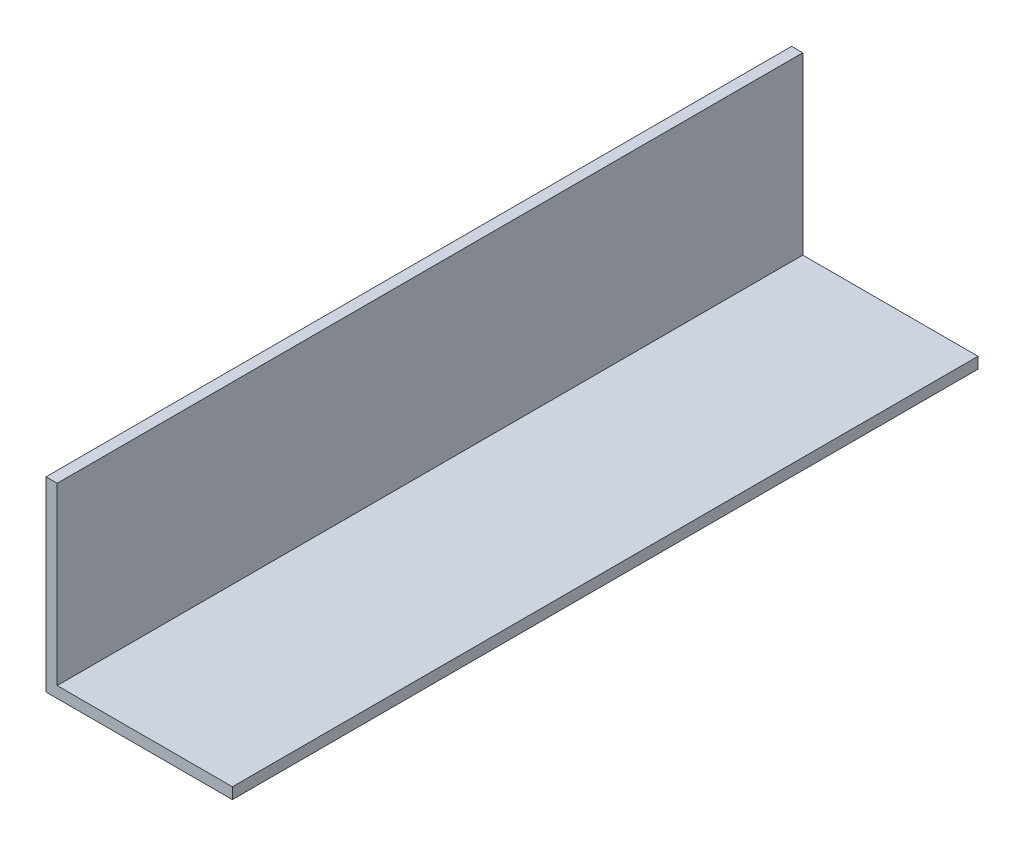
SolidWorks part; units mm, degrees
ref_plane "Front Plane" through (0, 0, 0) normal (0, 0, 1) x (1, 0, 0)
ref_plane "Top Plane" through (0, 0, 0) normal (0, 1, 0) x (1, 0, 0)
ref_plane "Right Plane" through (0, 0, 0) normal (1, 0, 0) x (0, 0, -1)
sketch "Sketch1" plane through (0, 0, 0) normal (0, 0, 1) x (1, 0, 0)
  line L0 (0, 0) -> (0, 25)
  line L1 (0, 25) -> (1.5, 25)
  line L2 (1.5, 25) -> (1.5, 1.5)
  line L3 (1.5, 1.5) -> (25, 1.5)
  line L4 (25, 1.5) -> (25, 0)
  line L5 (25, 0) -> (0, 0)
  dimension "D1" = 1.5
  dimension "D2" = 25
extrude "Boss-Extrude1" add sketch "Sketch1" along normal blind 100
